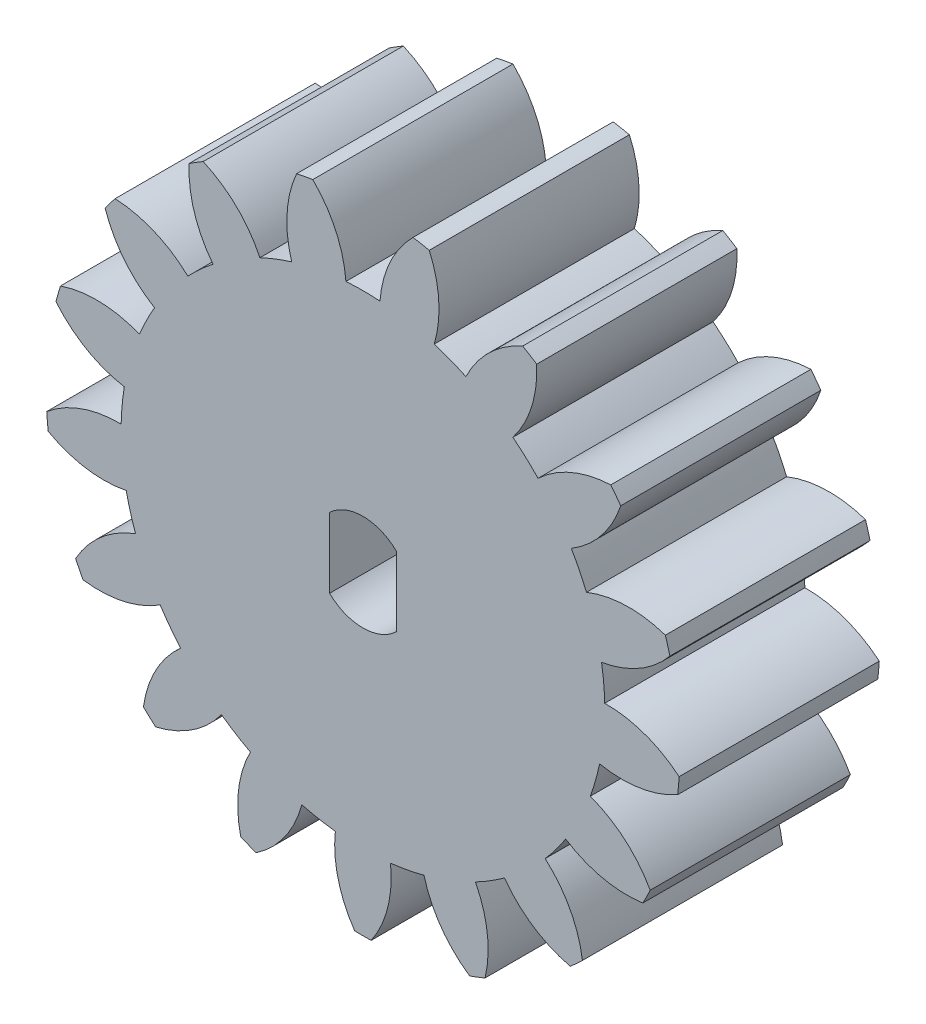
SolidWorks part; units mm, degrees
material "ABS"
ref_plane "Alzado" through (0, 0, 0) normal (0, 0, 1) x (1, 0, 0)
ref_plane "Planta" through (0, 0, 0) normal (0, 1, 0) x (1, 0, 0)
ref_plane "Vista lateral" through (0, 0, 0) normal (1, 0, 0) x (0, 0, -1)
sketch "Croquis2" plane through (0, 0, 0) normal (0, 0, 1) x (1, 0, 0)
  arc A0 (-18.4039, 4.8415) -> (-14.3072, 2.47) centre (-13.1617, 9.1728) ccw
  arc A1 (-14.3072, 2.47) -> (-14.4955, 0.438) centre (0, 0.1195) ccw
  arc A2 (-14.4955, 0.438) -> (-18.9582, -1.1405) centre (-14.6012, -6.3612) ccw
  arc A3 (-18.9582, -1.1405) -> (-18.8669, -2.1256) centre (0, 0.1195) ccw
  arc A4 (-18.8669, -2.1256) -> (-14.1902, -2.8571) centre (-15.5434, 3.8069) ccw
  arc A5 (-14.1902, -2.8571) -> (-13.6317, -4.8199) centre (0, 0.1195) ccw
  arc A6 (-13.6317, -4.8199) -> (-17.2228, -7.9039) centre (-11.2741, -11.1981) ccw
  arc A7 (-17.2228, -7.9039) -> (-16.7818, -8.7895) centre (0, 0.1195) ccw
  arc A8 (-16.7818, -8.7895) -> (-12.1567, -7.7822) centre (-15.8258, -2.0571) ccw
  arc A9 (-12.1567, -7.7822) -> (-10.9269, -9.4107) centre (0, 0.1195) ccw
  arc A10 (-10.9269, -9.4107) -> (-13.1615, -13.5837) centre (-6.4244, -14.5066) ccw
  arc A11 (-13.1615, -13.5837) -> (-12.4303, -14.2502) centre (0, 0.1195) ccw
  arc A12 (-12.4303, -14.2502) -> (-8.4813, -11.6401) centre (-13.9709, -7.627) ccw
  arc A13 (-8.4813, -11.6401) -> (-6.7463, -12.7144) centre (0, 0.1195) ccw
  arc A14 (-6.7463, -12.7144) -> (-7.3225, -17.4128) centre (-0.707, -15.8396) ccw
  arc A15 (-7.3225, -17.4128) -> (-6.4, -17.7702) centre (0, 0.1195) ccw
  arc A16 (-6.4, -17.7702) -> (-3.6606, -13.9098) centre (-10.2291, -12.1508) ccw
  arc A17 (-3.6606, -13.9098) -> (-1.6546, -14.2848) centre (0, 0.1195) ccw
  arc A18 (-1.6546, -14.2848) -> (-0.4947, -18.8741) centre (5.1058, -15.0174) ccw
  arc A19 (-0.4947, -18.8741) -> (0.4947, -18.8741) centre (0, 0.1195) ccw
  arc A20 (0.4947, -18.8741) -> (1.6546, -14.2848) centre (-5.1058, -15.0174) ccw
  arc A21 (1.6546, -14.2848) -> (3.6606, -13.9098) centre (0, 0.1195) ccw
  arc A22 (3.6606, -13.9098) -> (6.4, -17.7702) centre (10.2291, -12.1508) ccw
  arc A23 (6.4, -17.7702) -> (7.3225, -17.4128) centre (0, 0.1195) ccw
  arc A24 (7.3225, -17.4128) -> (6.7463, -12.7144) centre (0.707, -15.8396) ccw
  arc A25 (6.7463, -12.7144) -> (8.4813, -11.6401) centre (0, 0.1195) ccw
  arc A26 (8.4813, -11.6401) -> (12.4303, -14.2502) centre (13.9709, -7.627) ccw
  arc A27 (12.4303, -14.2502) -> (13.1615, -13.5837) centre (0, 0.1195) ccw
  arc A28 (13.1615, -13.5837) -> (10.9269, -9.4107) centre (6.4244, -14.5066) ccw
  arc A29 (10.9269, -9.4107) -> (12.1567, -7.7822) centre (0, 0.1195) ccw
  arc A30 (12.1567, -7.7822) -> (16.7818, -8.7895) centre (15.8258, -2.0571) ccw
  arc A31 (16.7818, -8.7895) -> (17.2228, -7.9039) centre (0, 0.1195) ccw
  arc A32 (17.2228, -7.9039) -> (13.6317, -4.8199) centre (11.2741, -11.1981) ccw
  arc A33 (13.6317, -4.8199) -> (14.1902, -2.8571) centre (0, 0.1195) ccw
  arc A34 (14.1902, -2.8571) -> (18.8669, -2.1256) centre (15.5434, 3.8069) ccw
  arc A35 (18.8669, -2.1256) -> (18.9582, -1.1405) centre (0, 0.1195) ccw
  arc A36 (18.9582, -1.1405) -> (14.4955, 0.438) centre (14.6012, -6.3612) ccw
  arc A37 (14.4955, 0.438) -> (14.3072, 2.47) centre (0, 0.1195) ccw
  arc A38 (14.3072, 2.47) -> (18.4039, 4.8415) centre (13.1617, 9.1728) ccw
  arc A39 (18.4039, 4.8415) -> (18.1331, 5.7931) centre (0, 0.1195) ccw
  arc A40 (18.1331, 5.7931) -> (13.4016, 5.6528) centre (15.9563, -0.649) ccw
  arc A41 (13.4016, 5.6528) -> (12.492, 7.4796) centre (0, 0.1195) ccw
  arc A42 (12.492, 7.4796) -> (15.4553, 11.1709) centre (9.0025, 13.316) ccw
  arc A43 (15.4553, 11.1709) -> (14.8591, 11.9604) centre (0, 0.1195) ccw
  arc A44 (14.8591, 11.9604) -> (10.4977, 10.1204) centre (15.1564, 5.1669) ccw
  arc A45 (10.4977, 10.1204) -> (8.9896, 11.4952) centre (0, 0.1195) ccw
  arc A46 (8.9896, 11.4952) -> (10.4194, 16.0077) centre (3.6275, 15.6769) ccw
  arc A47 (10.4194, 16.0077) -> (9.5782, 16.5285) centre (0, 0.1195) ccw
  arc A48 (9.5782, 16.5285) -> (6.1761, 13.2373) centre (12.3096, 10.3012) ccw
  arc A49 (6.1761, 13.2373) -> (4.2732, 13.9745) centre (0, 0.1195) ccw
  arc A50 (4.2732, 13.9745) -> (3.9763, 18.6987) centre (-2.2375, 15.9368) ccw
  arc A51 (3.9763, 18.6987) -> (3.0038, 18.8805) centre (0, 0.1195) ccw
  arc A52 (3.0038, 18.8805) -> (1.0204, 14.5825) centre (7.8003, 14.0604) ccw
  arc A53 (1.0204, 14.5825) -> (-1.0204, 14.5825) centre (0, 0.1195) ccw
  arc A54 (-1.0204, 14.5825) -> (-3.0038, 18.8805) centre (-7.8003, 14.0604) ccw
  arc A55 (-3.0038, 18.8805) -> (-3.9763, 18.6987) centre (0, 0.1195) ccw
  arc A56 (-3.9763, 18.6987) -> (-4.2732, 13.9745) centre (2.2375, 15.9368) ccw
  arc A57 (-4.2732, 13.9745) -> (-6.1761, 13.2373) centre (0, 0.1195) ccw
  arc A58 (-6.1761, 13.2373) -> (-9.5782, 16.5285) centre (-12.3096, 10.3012) ccw
  arc A59 (-9.5782, 16.5285) -> (-10.4194, 16.0077) centre (0, 0.1195) ccw
  arc A60 (-10.4194, 16.0077) -> (-8.9896, 11.4952) centre (-3.6275, 15.6769) ccw
  arc A61 (-8.9896, 11.4952) -> (-10.4977, 10.1204) centre (0, 0.1195) ccw
  arc A62 (-10.4977, 10.1204) -> (-14.8591, 11.9604) centre (-15.1564, 5.1669) ccw
  arc A63 (-14.8591, 11.9604) -> (-15.4553, 11.1709) centre (0, 0.1195) ccw
  arc A64 (-15.4553, 11.1709) -> (-12.492, 7.4796) centre (-9.0025, 13.316) ccw
  arc A65 (-12.492, 7.4796) -> (-13.4016, 5.6528) centre (0, 0.1195) ccw
  arc A66 (-13.4016, 5.6528) -> (-18.1331, 5.7931) centre (-15.9563, -0.649) ccw
  arc A67 (-18.1331, 5.7931) -> (-18.4039, 4.8415) centre (0, 0.1195) ccw
  dimension "D1" = 19
  dimension "D2" = 14.499
extrude "Saliente-Extruir1" add sketch "Croquis2" along normal blind 12
sketch "Croquis3" plane through (0, 0, 12) normal (0, 0, 1) x (1, 0, 0)
  line L0 (-2, -2.1) -> (-2, 2.1)
  line L1 (0, 0) -> (0, 2.9) construction
  line L2 (2, -2.1) -> (2, 2.1)
  arc A0 (-2, -2.1) -> (2, -2.1) centre (0, 0) ccw
  arc A1 (2, 2.1) -> (-2, 2.1) centre (0, 0) ccw
  dimension "D1" = 5.8
  dimension "D2" = 4
extrude "Cortar-Extruir1" cut sketch "Croquis3" against normal through all both and the other way through all
sketch "Croquis4" plane through (0, 0, 12) normal (0, 0, 1) x (1, 0, 0)
  circle A0 centre (0, 0) radius 14.5
  dimension "D1" = 29
